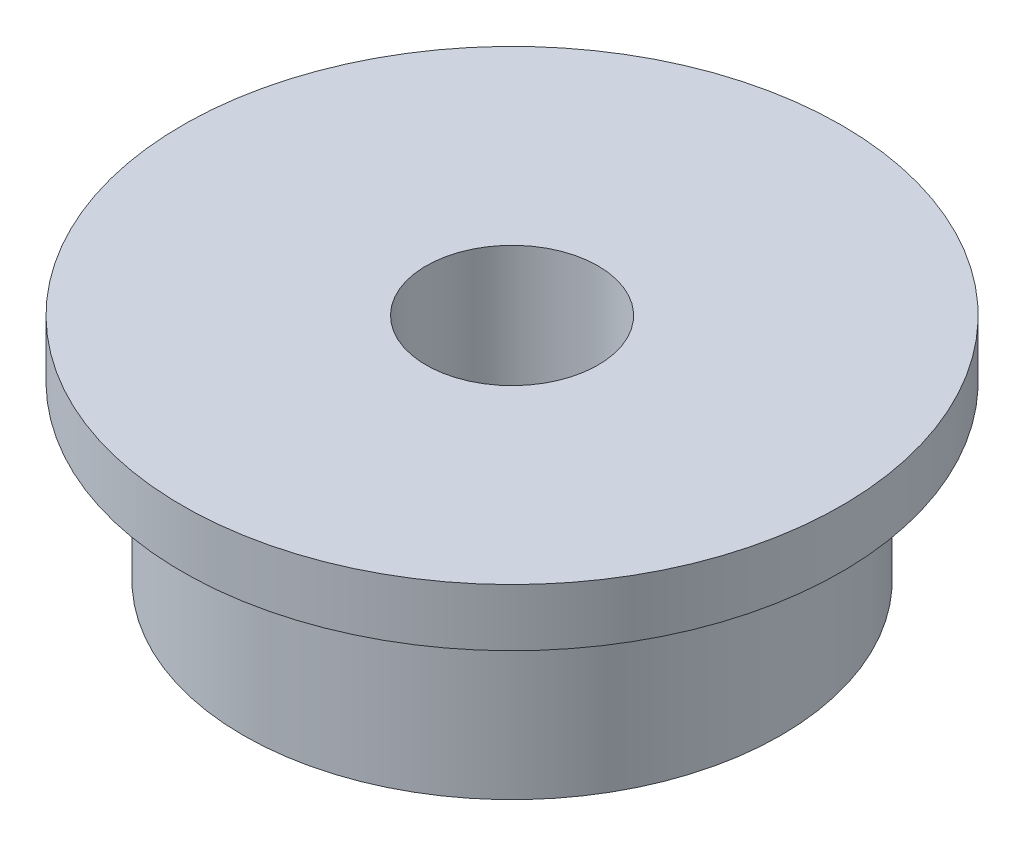
SolidWorks part; units mm, degrees
material "Chrome Stainless Steel"
ref_plane "Front Plane" through (0, 0, 0) normal (0, 0, 1) x (1, 0, 0)
ref_plane "Top Plane" through (0, 0, 0) normal (0, 1, 0) x (1, 0, 0)
ref_plane "Right Plane" through (0, 0, 0) normal (1, 0, 0) x (0, 0, -1)
sketch "Sketch1" plane through (0, 0, 0) normal (0, 0, 1) x (1, 0, 0)
  line L0 (0, 0) -> (0, 5.1467) construction
  line L7 (-1.5, 0.5434) -> (-1.5, 4.5434)
  line L8 (-1.5, 4.5434) -> (-5.75, 4.5434)
  line L9 (-5.75, 4.5434) -> (-5.75, 3.5434)
  line L10 (-5.75, 3.5434) -> (-4.69, 3.5434)
  line L11 (-4.69, 3.5434) -> (-4.69, 0.5434)
  line L12 (-4.69, 0.5434) -> (-1.5, 0.5434)
  dimension "D1" = 4
  dimension "D2" = 1
  dimension "D3" = 5.75
  dimension "D4" = 1.5
  dimension "D5" = 4.69
revolve "Revolve1" add sketch "Sketch1" angle 360 about L0
